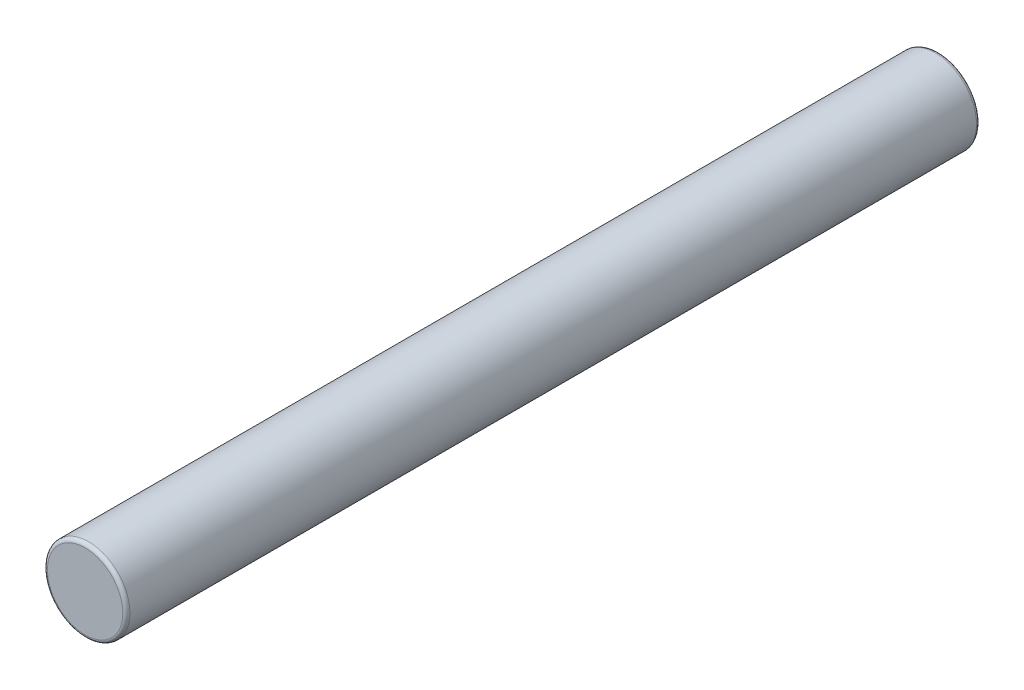
SolidWorks part; units mm, degrees
ref_plane "Front Plane" through (0, 0, 0) normal (0, 0, 1) x (1, 0, 0)
ref_plane "Top Plane" through (0, 0, 0) normal (0, 1, 0) x (1, 0, 0)
ref_plane "Right Plane" through (0, 0, 0) normal (1, 0, 0) x (0, 0, -1)
sketch "Sketch1" plane through (0, 0, 0) normal (0, 0, 1) x (1, 0, 0)
  circle A0 centre (0, 0) radius 2.9
  dimension "D1" = 5.8
extrude "Boss-Extrude1" add sketch "Sketch1" along normal blind 60
sketch "Sketch2" plane through (0, 0, 60) normal (0, 0, 1) x (1, 0, 0)
  circle A0 centre (0, 0) radius 3
fillet "Fillet4" radius 0.25 2 edges at (2.9, 0, 60) (2.9, 0, 0)
